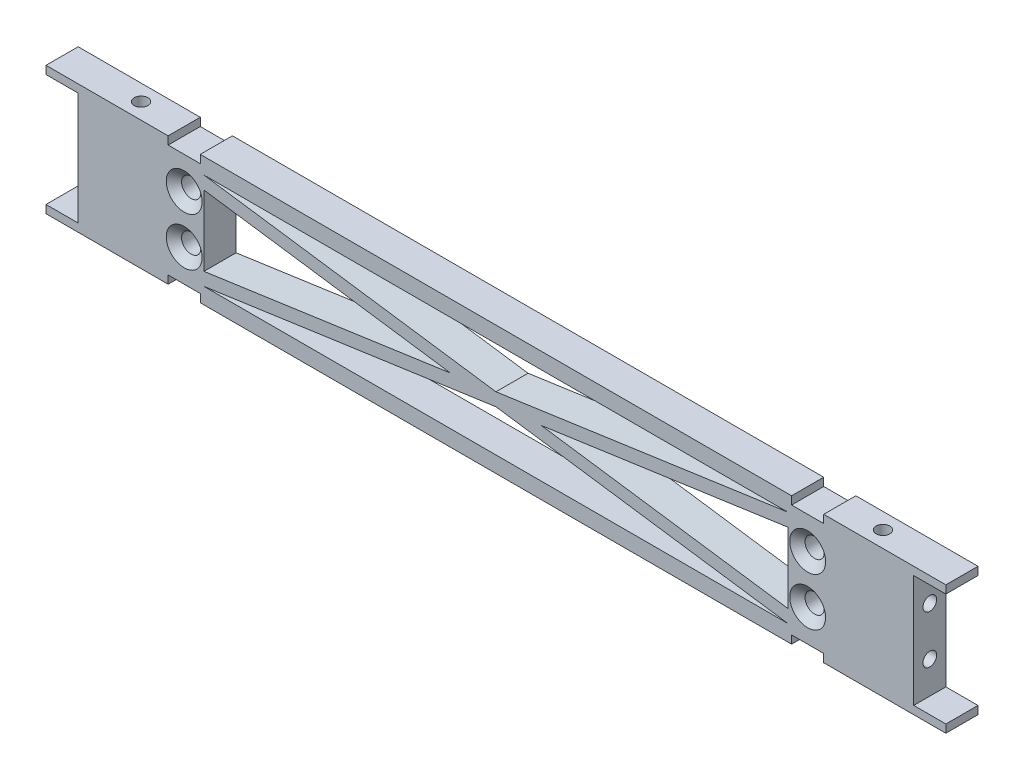
SolidWorks part; units mm, degrees
material "6061-T6 (SS)"
ref_plane "Front Plane" through (0, 0, 0) normal (0, 0, 1) x (1, 0, 0)
ref_plane "Top Plane" through (0, 0, 0) normal (0, 1, 0) x (1, 0, 0)
ref_plane "Right Plane" through (0, 0, 0) normal (1, 0, 0) x (0, 0, -1)
sketch "Sketch1" plane through (0, 0, 0) normal (0, 0, 1) x (1, 0, 0)
  line L0 (0, 12.7) -> (0, -12.7) construction
  line L1 (-88.9, 12.7) -> (88.9, 12.7)
  line L2 (-88.9, 12.7) -> (-88.9, 11.1125)
  line L3 (-88.9, -12.7) -> (88.9, -12.7)
  line L4 (88.9, 12.7) -> (88.9, 11.1125)
  line L5 (-88.9, 12.7) -> (88.9, -12.7) construction
  line L6 (-88.9, -12.7) -> (88.9, 12.7) construction
  line L7 (-88.9, 11.1125) -> (-82.55, 11.1125)
  line L8 (88.9, -11.1125) -> (82.55, -11.1125)
  line L9 (-88.9, -11.1125) -> (-82.55, -11.1125)
  line L10 (-82.55, 11.1125) -> (-82.55, -11.1125)
  line L11 (-88.9, -11.1125) -> (-88.9, -12.7)
  line L12 (82.55, 11.1125) -> (82.55, -11.1125)
  line L13 (88.9, 11.1125) -> (82.55, 11.1125)
  line L14 (88.9, -11.1125) -> (88.9, -12.7)
  line L15 (-89.0796, 11.4428) -> (88.7204, -13.9572)
  line L16 (-88.7204, -13.9572) -> (89.0796, 11.4428)
  line L17 (-88.7204, 13.9572) -> (89.0796, -11.4428)
  line L18 (-89.0796, -11.4428) -> (88.7204, 13.9572)
  line L20 (-57.6947, 9.525) -> (57.6947, 9.525)
  line L21 (-57.6947, 9.525) -> (-57.6947, -9.525)
  line L22 (-57.6947, -9.525) -> (57.6947, -9.525)
  line L23 (57.6947, 9.525) -> (57.6947, -9.525)
  point P0 (0, 0)
  dimension "D1" = 177.8
  dimension "D2" = 25.4
  dimension "D3" = 6.35
  dimension "D4" = 1.5875
  dimension "D5" = 1.5875
  dimension "D8" = 3.175
  dimension "D9" = 3.175
  dimension "D6" = 1.27
  dimension "D7" = 1.27
extrude "Boss-Extrude1" add sketch "Sketch1" along normal blind 6.35 contours L21 L15 L10 L18 | L22 L16 L3 L15 | L21 L18 L10 L9 L11 L3 L16 | L18 L21 L16 L15 | L17 L21 L15 L18 | L17 L20 L18 L1 | L21 L17 L1 L2 L15 L7 L10 | L23 L17 L16 L15 | L23 L18 L17 L16 | L18 L15 L16 L17 | L17 L23 L15 L3 L14 L8 L12 | L18 L23 L16 L12 L13 L4 L1 | L16 L13 L4 | L8 L17 L14 | L16 L23 L17 L12 | L11 L18 L9 | L15 L2 L7
ref_plane "Plane1" through (0, 0, 0) normal (1, 0, 0) x (0, 0, -1)
hole_wizard "Tap Drill for #6-32 Tap1" positions "Sketch3" profile "Sketch4" hole size "#6-32" standard "ANSI Inch"
sketch "Sketch3" plane through (-82.55, 0, 0) normal (-1, 0, 0) x (0, 0, 1)
  line L0 (6.35, 11.1125) -> (0, 11.1125) construction
  line L1 (0, 11.1125) -> (0, -11.1125) construction
  point P0 (3.175, 4.7625)
  point P2 (3.175, -4.7625)
  dimension "D1" = 6.35
  dimension "D2" = 6.35
  dimension "D3" = 3.175
  dimension "D4" = 3.175
sketch "Sketch4" plane through (-82.55, 4.7625, 3.175) normal (0, 1, 0) x (0, 0, 1)
  line L0 (0, 0) -> (0, 13.5127)
  line L1 (0, 13.5127) -> (1.3525, 12.7)
  line L2 (1.3525, 12.7) -> (1.3525, 0)
  line L5 (1.3525, 0) -> (0, 0)
  line L10 (0, 13.5127) -> (-1.3526, 12.7) construction
  line L11 (0, -6.35) -> (0, 107.95) construction
  dimension "Hole Dia." = 2.7051
  dimension "Hole Depth" = 12.7
  dimension "Drill Angle" = 118
mirror "Mirror1" about plane through (0, 0, 0) normal (1, 0, 0) of "Tap Drill for #6-32 Tap1"
hole_wizard "Tap Drill for #6-32 Tap2" positions "Sketch6" profile "Sketch5" hole size "#6-32" standard "ANSI Inch"
sketch "Sketch6" plane through (0, 12.7, 0) normal (0, 1, 0) x (1, 0, 0)
  line L0 (-88.9, -6.35) -> (-88.9, 0) construction
  point P0 (-73.2896, -3.175)
  point P9 (-88.9, -3.175)
  dimension "D1" = 15.6104
sketch "Sketch5" plane through (-73.2896, 12.7, 3.175) normal (1, 0, 0) x (0, 0, 1)
  line L0 (0, 0) -> (0, 7.1627)
  line L1 (0, 7.1627) -> (1.3525, 6.35)
  line L2 (1.3525, 6.35) -> (1.3525, 0)
  line L5 (1.3525, 0) -> (0, 0)
  line L10 (0, 7.1627) -> (-1.3526, 6.35) construction
  line L11 (0, -6.35) -> (0, 107.95) construction
  dimension "Hole Dia." = 2.7051
  dimension "Hole Depth" = 6.35
  dimension "Drill Angle" = 118
ref_plane "Plane2" through (0, 0, 0) normal (0, -1, 0) x (-1, 0, 0)
mirror "Mirror2" about plane through (0, 0, 0) normal (1, 0, 0) of "Tap Drill for #6-32 Tap2"
mirror "Mirror3" about plane through (0, 0, 0) normal (0, -1, 0) of "Mirror2", "Tap Drill for #6-32 Tap2"
sketch "Sketch7" plane through (0, 0, 6.35) normal (0, 0, 1) x (1, 0, 0)
  line L0 (-64.77, 11.1125) -> (-58.42, 11.1125) construction
  line L1 (-64.77, 11.1125) -> (-64.77, 12.7) construction
  line L2 (-58.42, 11.1125) -> (-58.42, 12.7) construction
  line L3 (-64.77, 12.7) -> (-58.42, 12.7) construction
  line L4 (-64.77, -11.1125) -> (-58.42, -11.1125) construction
  line L5 (-64.77, -12.7) -> (-64.77, -11.1125) construction
  line L6 (-88.9, -12.7) -> (88.9, -12.7) construction
  line L7 (-58.42, -12.7) -> (-58.42, -11.1125) construction
  line L8 (58.42, -11.1125) -> (58.42, -12.7) construction
  line L9 (64.77, -11.1125) -> (58.42, -11.1125) construction
  line L10 (64.77, -11.1125) -> (64.77, -12.7) construction
  line L11 (58.42, 12.7) -> (58.42, 11.1125) construction
  line L12 (64.77, 11.1125) -> (58.42, 11.1125) construction
  line L13 (64.77, 12.7) -> (64.77, 11.1125) construction
  line L14 (64.77, 12.7) -> (58.42, 12.7) construction
  line L15 (-64.77, 11.1125) -> (-58.42, 11.1125)
  line L16 (-64.77, 11.1125) -> (-64.77, 12.7)
  line L17 (-58.42, 11.1125) -> (-58.42, 12.7)
  line L18 (-64.77, 12.7) -> (-58.42, 12.7)
  line L19 (-64.77, -11.1125) -> (-58.42, -11.1125)
  line L20 (-64.77, -12.7) -> (-64.77, -11.1125)
  line L21 (-64.77, -12.7) -> (-58.42, -12.7)
  line L22 (-58.42, -12.7) -> (-58.42, -11.1125)
  line L23 (58.42, -11.1125) -> (58.42, -12.7)
  line L24 (64.77, -11.1125) -> (58.42, -11.1125)
  line L25 (64.77, -11.1125) -> (64.77, -12.7)
  line L26 (58.42, 12.7) -> (58.42, 11.1125)
  line L27 (64.77, 11.1125) -> (58.42, 11.1125)
  line L28 (64.77, 12.7) -> (64.77, 11.1125)
  line L29 (64.77, 12.7) -> (58.42, 12.7)
  line L30 (58.42, -12.7) -> (64.77, -12.7)
extrude "Cut-Extrude1" cut sketch "Sketch7" against normal through all
hole_wizard "CSK for #6 Flat Head Machine Screw (100)1" positions "Sketch9" profile "Sketch8" countersink size "#6" standard "ANSI Inch" end condition through all
sketch "Sketch9" plane through (0, 0, 6.35) normal (0, 0, 1) x (1, 0, 0)
  line L0 (-64.77, 11.1125) -> (-58.42, 11.1125) construction
  line L1 (0, 12.7) -> (0, -12.7) construction
  line L2 (-58.42, 12.7) -> (58.42, 12.7) construction
  line L3 (-58.42, -12.7) -> (58.42, -12.7) construction
  point P0 (-61.595, 4.7625)
  point P2 (-61.595, -4.7625)
  point P7 (-61.595, 11.1125)
  point P18 (61.595, -4.7625)
  point P19 (61.595, 4.7625)
  dimension "D1" = 7.9375
  dimension "D2" = 7.9375
sketch "Sketch8" plane through (-61.595, 4.7625, 6.35) normal (1, 0, 0) x (0, -1, 0)
  line L0 (0, 0) -> (0, 6.35)
  line L1 (0, 6.35) -> (1.8986, 6.35)
  line L2 (1.8986, 6.35) -> (1.8986, 1.38)
  line L3 (1.8986, 1.38) -> (3.5433, 0)
  line L5 (3.5433, 0) -> (0, 0)
  line L6 (-1.8986, 1.38) -> (-3.5433, 0) construction
  line L11 (0, -6.35) -> (0, 107.95) construction
  dimension "Thru Hole Dia." = 3.7973
  dimension "Thru Hole Depth" = 6.35
  dimension "Near C'Sink Dia." = 7.0866
  dimension "Near C'Sink Angle" = 100
equation "\"D9@Sketch1\"=\"D8@Sketch1\""
